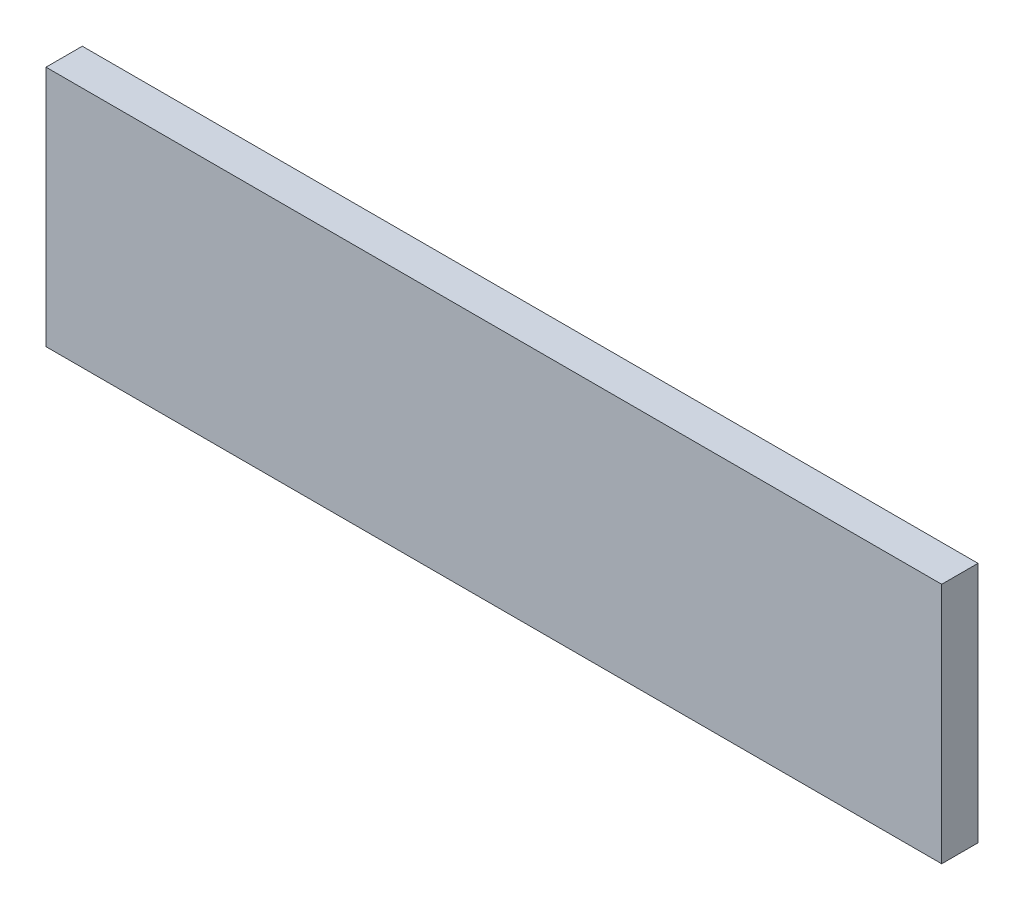
SolidWorks part; units mm, degrees
ref_plane "Front Plane" through (0, 0, 0) normal (0, 0, 1) x (1, 0, 0)
ref_plane "Top Plane" through (0, 0, 0) normal (0, 1, 0) x (1, 0, 0)
ref_plane "Right Plane" through (0, 0, 0) normal (1, 0, 0) x (0, 0, -1)
sketch "Sketch2" plane through (0, 0, 0) normal (0, 0, 1) x (1, 0, 0)
  line L1 (-37, -10) -> (37, -10)
  line L2 (-37, -10) -> (-37, 10)
  line L3 (-37, 10) -> (37, 10)
  line L4 (37, -10) -> (37, 10)
  line L5 (-37, -10) -> (37, 10) construction
  line L6 (-37, 10) -> (37, -10) construction
  point P0 (0, 0)
  dimension "D1" = 74
  dimension "D2" = 20
extrude "Boss-Extrude1" add sketch "Sketch2" along normal blind 3
